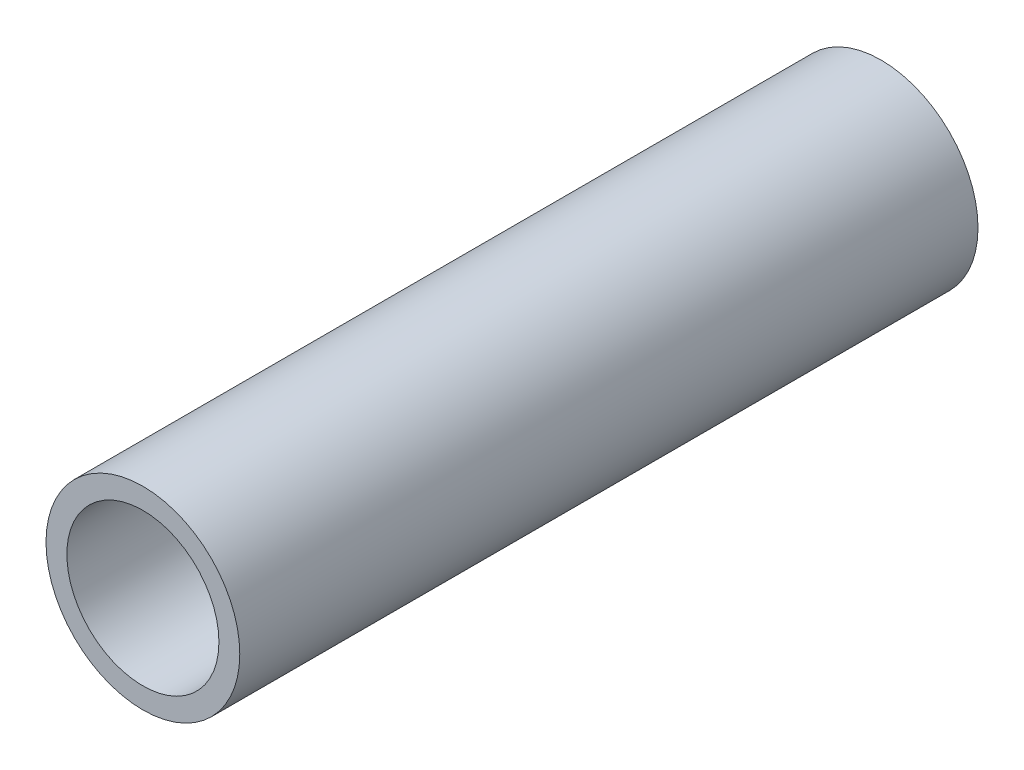
SolidWorks part; units mm, degrees
ref_plane "Front Plane" through (0, 0, 0) normal (0, 0, 1) x (1, 0, 0)
ref_plane "Top Plane" through (0, 0, 0) normal (0, 1, 0) x (1, 0, 0)
ref_plane "Right Plane" through (0, 0, 0) normal (1, 0, 0) x (0, 0, -1)
sketch "Sketch1" plane through (0, 0, 0) normal (0, 0, 1) x (1, 0, 0)
  circle A0 centre (0, 0) radius 10.4648
  circle A1 centre (0, 0) radius 13.335
  dimension "D1" = 20.9296
  dimension "D2" = 26.67
extrude "Boss-Extrude1" add sketch "Sketch1" along normal mid plane 101.6
